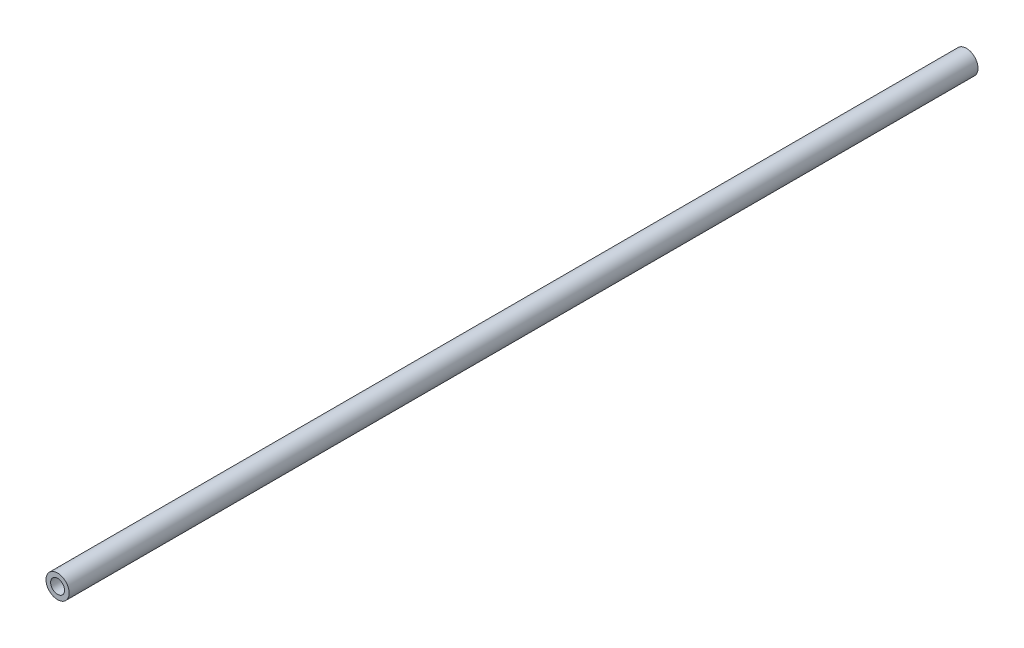
SolidWorks part; units mm, degrees
ref_plane "Front Plane" through (0, 0, 0) normal (0, 0, 1) x (1, 0, 0)
ref_plane "Top Plane" through (0, 0, 0) normal (0, 1, 0) x (1, 0, 0)
ref_plane "Right Plane" through (0, 0, 0) normal (1, 0, 0) x (0, 0, -1)
sketch "Sketch1" plane through (0, 0, 0) normal (0, 0, 1) x (1, 0, 0)
  circle A0 centre (0, 0) radius 0.635
extrude "Extrude1" add sketch "Sketch1" against normal blind 49.784
sketch "Sketch2" plane through (0, 0, 0) normal (0, 0, 1) x (1, 0, 0)
  circle A0 centre (0, 0) radius 0.381
extrude "Cut-Extrude1" cut sketch "Sketch2" against normal up to next
